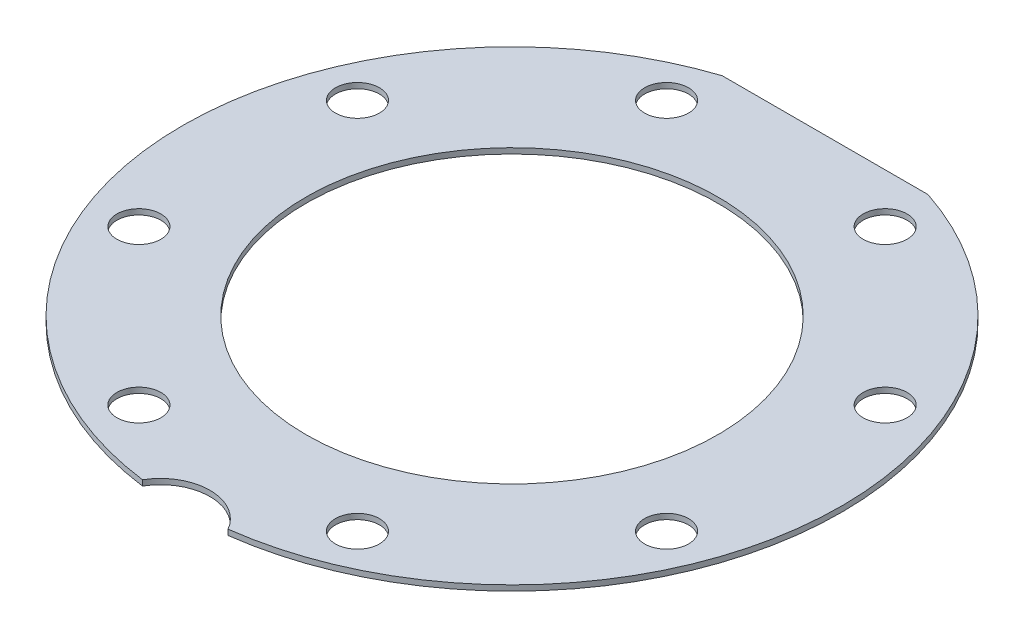
SolidWorks part; units mm, degrees
ref_plane "前视基准面" through (0, 0, 0) normal (0, 0, 1) x (1, 0, 0)
ref_plane "上视基准面" through (0, 0, 0) normal (0, 1, 0) x (1, 0, 0)
ref_plane "右视基准面" through (0, 0, 0) normal (1, 0, 0) x (0, 0, -1)
sketch "草图1" plane through (0, 0, 0) normal (0, 1, 0) x (1, 0, 0)
  line L0 (18.735, 57) -> (-18.735, 57)
  line L1 (0, 0) -> (-90.8139, 0) construction
  line L2 (0, 0) -> (-48.0417, 19.8995) construction
  arc A0 (-18.735, 57) -> (-7.7897, -59.4922) centre (0, 0) ccw
  circle A1 centre (0, 0) radius 37.5
  circle A2 centre (0, 0) radius 52 construction
  arc A3 (7.7897, -59.4922) -> (-7.7897, -59.4922) centre (0, -64) ccw
  arc A4 (7.7897, -59.4922) -> (18.735, 57) centre (0, 0) ccw
  circle A5 centre (-48.0417, 19.8995) radius 4
  circle A6 centre (-19.8995, 48.0417) radius 4
  circle A7 centre (19.8995, 48.0417) radius 4
  circle A8 centre (48.0417, 19.8995) radius 4
  circle A9 centre (48.0417, -19.8995) radius 4
  circle A10 centre (19.8995, -48.0417) radius 4
  circle A11 centre (-19.8995, -48.0417) radius 4
  circle A12 centre (-48.0417, -19.8995) radius 4
  dimension "D1" = 120
  dimension "D2" = 75
  dimension "D3" = 104
  dimension "D5" = 18
  dimension "D8" = 8
  dimension "D4" = 57
  dimension "D6" = 64
  dimension "D7" = 22.5
  dimension "D9" = 8
extrude "凸台-拉伸1" add sketch "草图1" along normal blind 1
